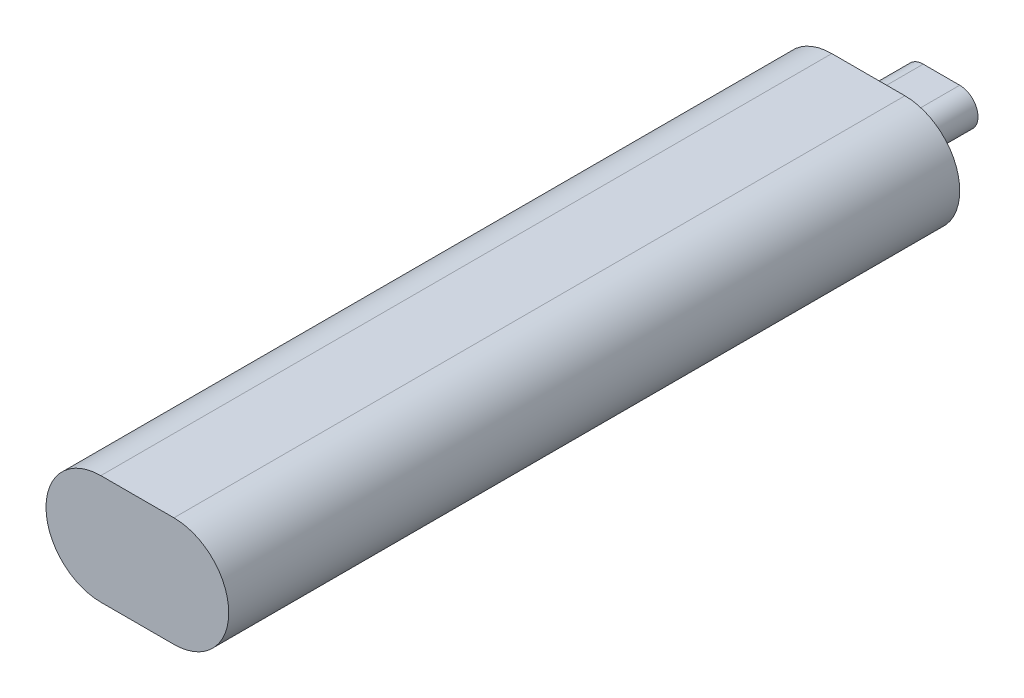
SolidWorks part; units mm, degrees
ref_plane "前视基准面" through (0, 0, 0) normal (0, 0, 1) x (1, 0, 0)
ref_plane "上视基准面" through (0, 0, 0) normal (0, 1, 0) x (1, 0, 0)
ref_plane "右视基准面" through (0, 0, 0) normal (1, 0, 0) x (0, 0, -1)
sketch "草图1" plane through (0, 0, 0) normal (0, 0, 1) x (1, 0, 0)
  line L0 (-10, 0) -> (10, 0) construction
  line L1 (-10, 15) -> (10, 15)
  line L2 (-10, -15) -> (10, -15)
  arc A0 (-10, 15) -> (-10, -15) centre (-10, 0) ccw
  arc A1 (10, -15) -> (10, 15) centre (10, 0) ccw
  point P3 (0, 0)
  point P8 (0, 0)
  dimension "D2" = 15
  dimension "D1" = 20
extrude "凸台-拉伸1" add sketch "草图1" along normal mid plane 200
sketch "草图2" plane through (0, 0, -100) normal (0, 0, -1) x (-1, 0, 0)
  line L0 (-5, 0) -> (5, 0) construction
  line L1 (-5, 5) -> (5, 5)
  line L2 (-5, -5) -> (5, -5)
  arc A0 (-5, 5) -> (-5, -5) centre (-5, 0) ccw
  arc A1 (5, -5) -> (5, 5) centre (5, 0) ccw
  point P3 (0, 0)
  point P8 (0, 0)
  dimension "D2" = 5
  dimension "D1" = 10
extrude "凸台-拉伸2" add sketch "草图2" along normal blind 20 contours A0 L2 A1 L1
